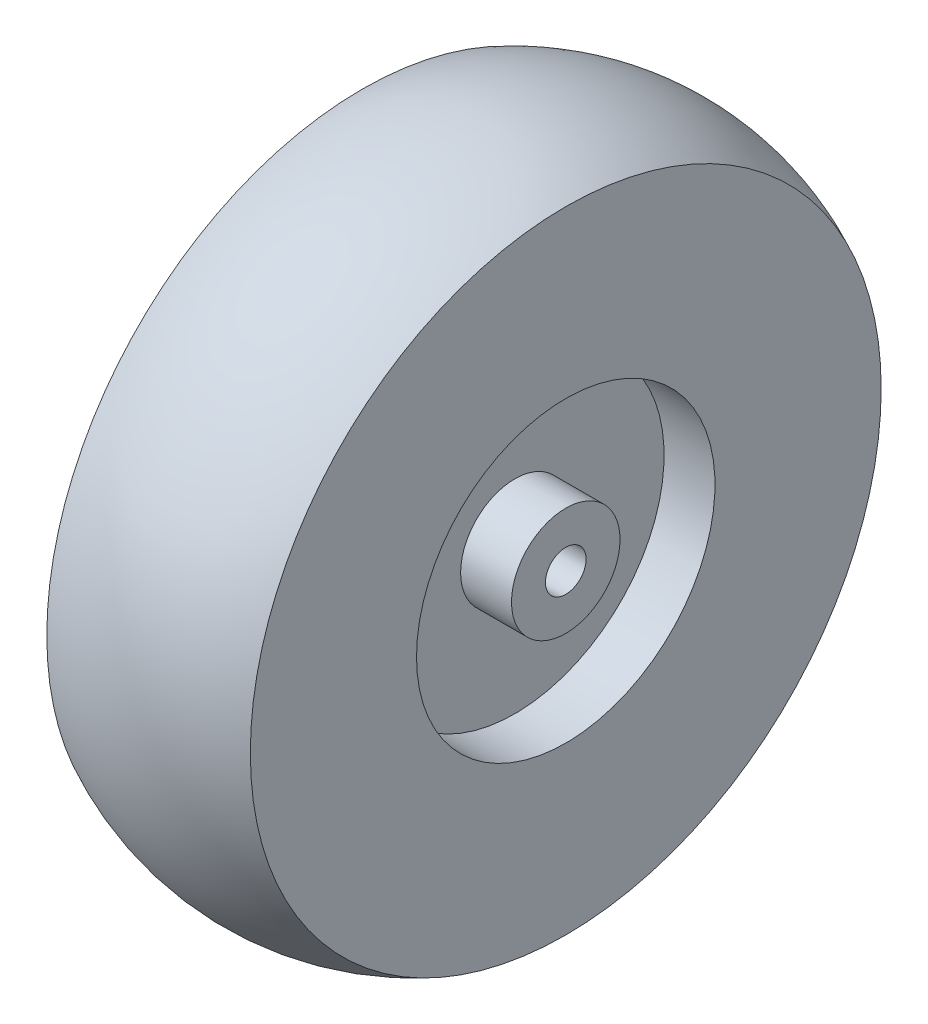
SolidWorks part; units mm, degrees
ref_plane "Front" through (0, 0, 0) normal (0, 0, 1) x (1, 0, 0)
ref_plane "Top" through (0, 0, 0) normal (0, 1, 0) x (1, 0, 0)
ref_plane "Right" through (0, 0, 0) normal (1, 0, 0) x (0, 0, -1)
sketch "Sketch2" plane through (0, 0, 0) normal (0, 0, 1) x (1, 0, 0)
  line L0 (-108.7393, 0) -> (119.2101, 0) construction
  line L1 (-30, 6) -> (30, 6)
  line L2 (30, 6) -> (30, 16)
  line L3 (30, 16) -> (15, 16)
  line L4 (15, 16) -> (15, 44)
  line L5 (15, 44) -> (30, 44)
  line L6 (30, 44) -> (30, 93)
  line L7 (-30, 93) -> (-30, 44)
  line L8 (-30, 44) -> (-15, 44)
  line L9 (-15, 44) -> (-15, 16)
  line L10 (-15, 16) -> (-30, 16)
  line L11 (-30, 16) -> (-30, 6)
  arc A0 (30, 93) -> (-30, 93) centre (0, 32.2143) ccw
  point P14 (0, 6)
  point P17 (0, 0)
  point P18 (0, 100)
  point P19 (-22.5, 16)
  dimension "D1" = 100
  dimension "D2" = 6
  dimension "D3" = 10
  dimension "D4" = 30
  dimension "D5" = 15
  dimension "D6" = 7
  dimension "D7" = 44
  dimension "D8" = 60
revolve "Revolve1" add sketch "Sketch2" angle 360 about L0
